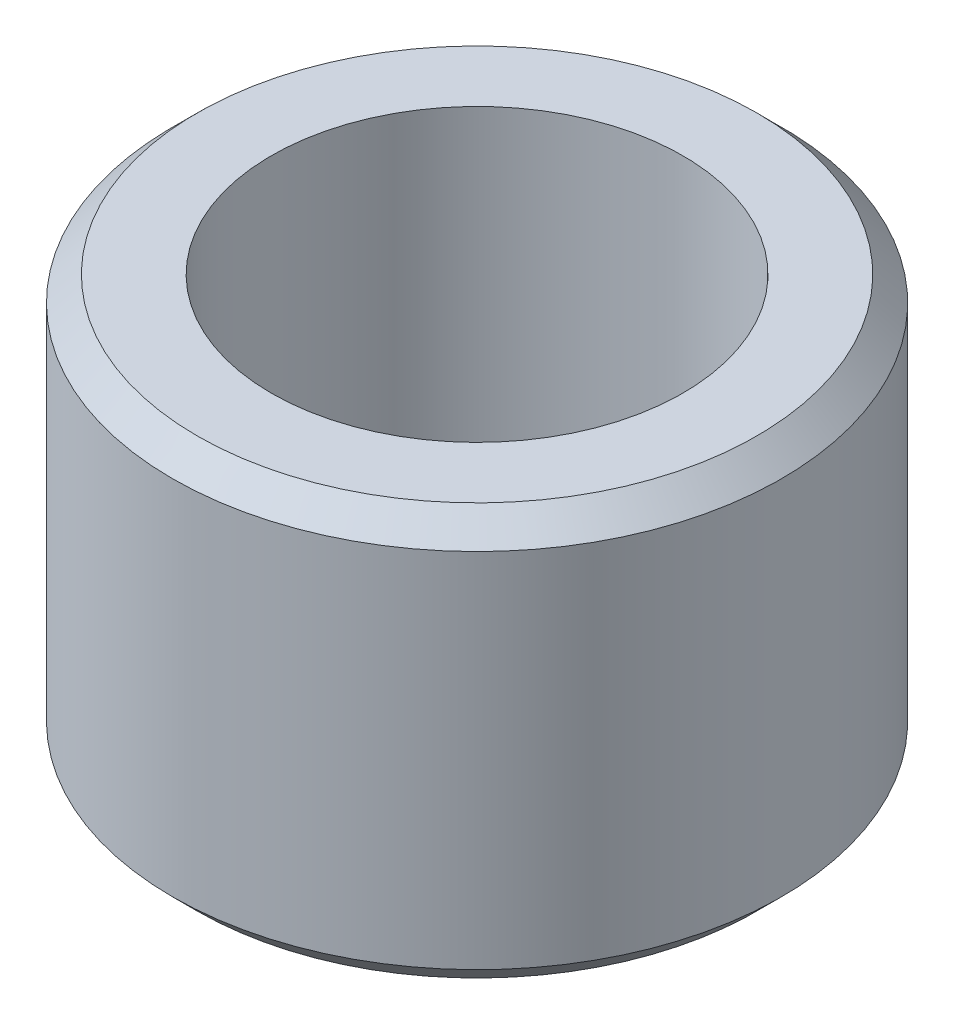
SolidWorks part; units mm, degrees
ref_plane "Front Plane" through (0, 0, 0) normal (0, 0, 1) x (1, 0, 0)
ref_plane "Top Plane" through (0, 0, 0) normal (0, 1, 0) x (1, 0, 0)
ref_plane "Right Plane" through (0, 0, 0) normal (1, 0, 0) x (0, 0, -1)
sketch "Sketch1" plane through (0, 0, 0) normal (0, 1, 0) x (1, 0, 0)
  circle A0 centre (0, 0) radius 2.5
  circle A1 centre (0, 0) radius 3.7
  dimension "D1" = 5
  dimension "D2" = 7.4
extrude "Boss-Extrude1" add sketch "Sketch1" along normal blind 5
chamfer "Chamfer1" distance 0.3 angle 45 2 edges at (0, 0, 3.7) (0, 5, 3.7)
